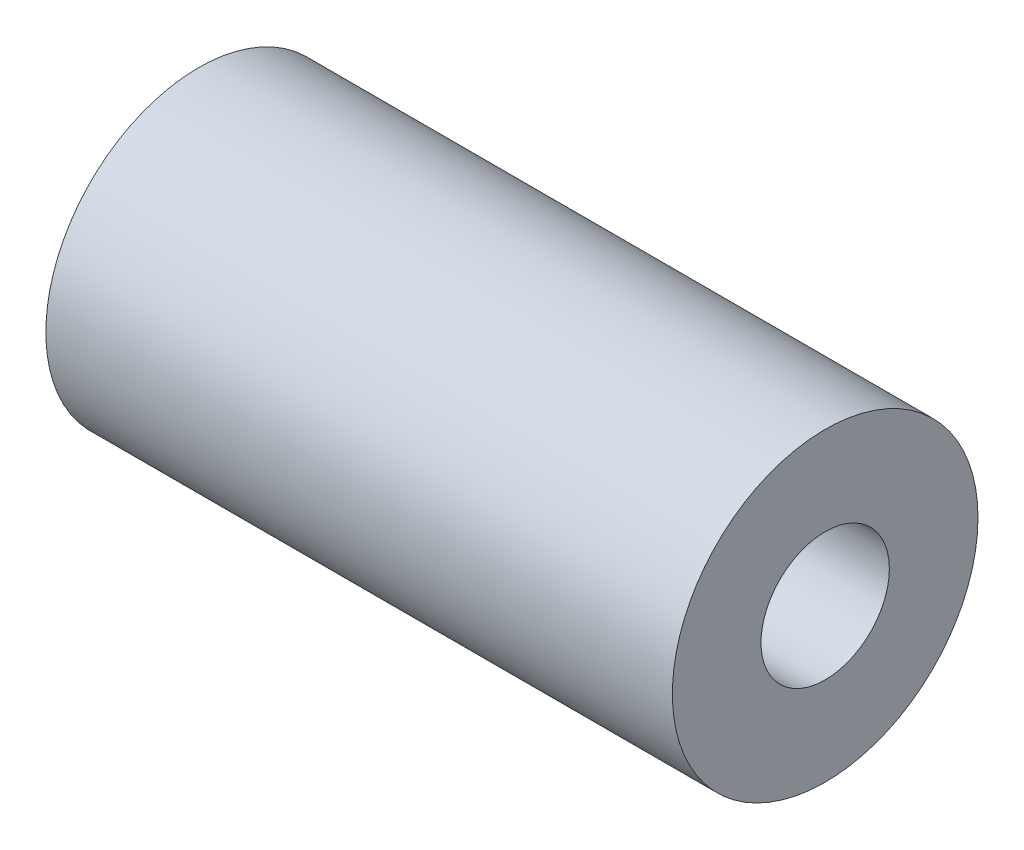
SolidWorks part; units mm, degrees
ref_plane "Front Plane" through (0, 0, 0) normal (0, 0, 1) x (1, 0, 0)
ref_plane "Top Plane" through (0, 0, 0) normal (0, 1, 0) x (1, 0, 0)
ref_plane "Right Plane" through (0, 0, 0) normal (1, 0, 0) x (0, 0, -1)
sketch "Sketch1" plane through (0, 0, 0) normal (1, 0, 0) x (0, 0, -1)
  circle A0 centre (0, 0) radius 10
  circle A1 centre (0, 0) radius 5 construction
  dimension "D1" = 20
  dimension "D2" = 10
extrude "Boss-Extrude1" add sketch "Sketch1" along normal blind 41
hole_wizard "Ø8.0mm Dowel Hole1" positions "Sketch2" profile "Sketch3" hole size "Ø8.0" standard "ANSI Metric" end condition through all
sketch "Sketch2" plane through (41, 0, 0) normal (1, 0, 0) x (0, 0, -1)
  point P0 (0, 0)
sketch "Sketch3" plane through (41, 0, 0) normal (0, 1, 0) x (0, 0, -1)
  line L0 (0, 0) -> (0, 41)
  line L1 (0, 41) -> (4.2, 41)
  line L2 (4.2, 41) -> (4.2, 0)
  line L5 (4.2, 0) -> (0, 0)
  line L11 (0, -6.35) -> (0, 107.95) construction
  dimension "Thru Hole Dia." = 8.4
  dimension "Thru Hole Depth" = 41
